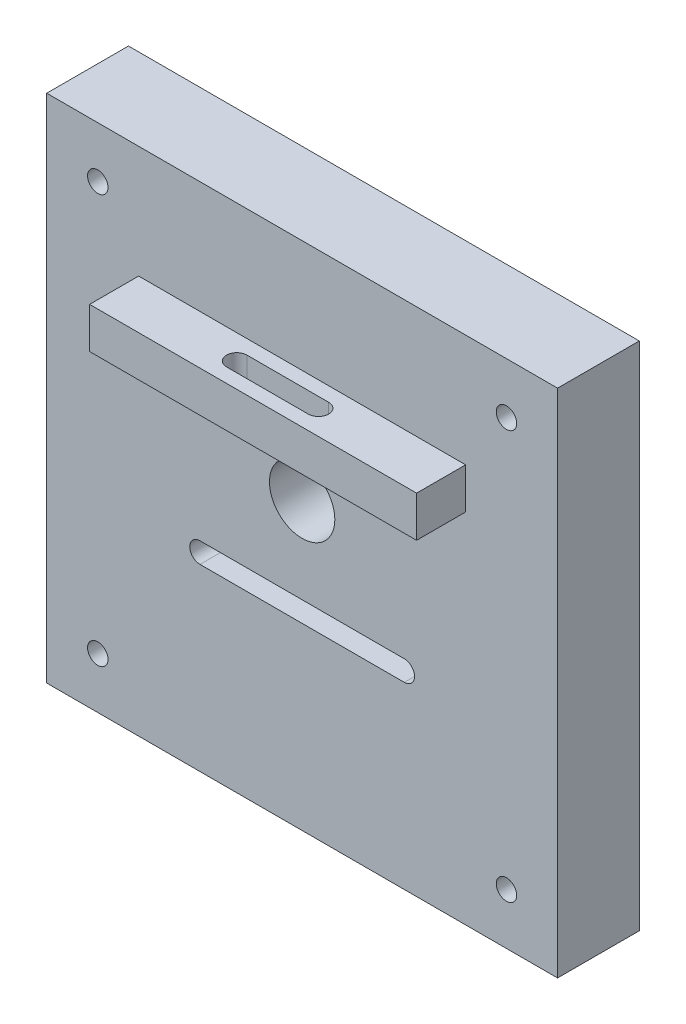
SolidWorks part; units mm, degrees
ref_plane "Front Plane" through (0, 0, 0) normal (0, 0, 1) x (1, 0, 0)
ref_plane "Top Plane" through (0, 0, 0) normal (0, 1, 0) x (1, 0, 0)
ref_plane "Right Plane" through (0, 0, 0) normal (1, 0, 0) x (0, 0, -1)
sketch "Sketch1" plane through (0, 0, 0) normal (0, 0, 1) x (1, 0, 0)
  line L1 (-58.3251, 63.7279) -> (66.6749, 63.7279)
  line L2 (-58.3251, 63.7279) -> (-58.3251, -61.2721)
  line L3 (-58.3251, -61.2721) -> (66.6749, -61.2721)
  line L4 (66.6749, 63.7279) -> (66.6749, -61.2721)
  dimension "D1" = 125
  dimension "D2" = 125
extrude "Boss-Extrude1" add sketch "Sketch1" along normal blind 20
sketch "Sketch2" plane through (0, 0, 20) normal (0, 0, 1) x (1, 0, 0)
  line L0 (-58.3251, 63.7279) -> (-58.3251, -61.2721) construction
  line L1 (66.6749, 63.7279) -> (-58.3251, 63.7279) construction
  circle A0 centre (-45.8251, 51.2279) radius 2.5
  circle A1 centre (54.1749, 51.2279) radius 2.5
  circle A2 centre (54.1749, -48.7721) radius 2.5
  circle A3 centre (-45.8251, -48.7721) radius 2.5
  dimension "D1" = 5
  dimension "D2" = 12.5
  dimension "D3" = 12.5
  dimension "D4" = 2
  dimension "D5" = 2
extrude "Cut-Extrude1" cut sketch "Sketch2" against normal through all
sketch "Sketch3" plane through (0, 0, 20) normal (0, 0, 1) x (1, 0, 0)
  line L0 (-58.3251, 63.7279) -> (-58.3251, -61.2721) construction
  line L1 (-35.8251, 26.2279) -> (44.1749, 26.2279) construction
  line L2 (-35.8251, 26.2279) -> (-35.8251, -23.7721) construction
  line L3 (-35.8251, -23.7721) -> (44.1749, -23.7721) construction
  line L4 (44.1749, 26.2279) -> (44.1749, -23.7721) construction
  line L5 (66.6749, 63.7279) -> (-58.3251, 63.7279) construction
  line L6 (-35.8251, -14.8721) -> (-16.8951, -14.8721) construction
  line L7 (4.1749, 26.2279) -> (4.1749, -12.3721) construction
  line L8 (-20.8251, -12.3721) -> (29.1749, -12.3721)
  line L10 (29.1749, -17.3721) -> (-20.8251, -17.3721)
  line L11 (4.1749, -14.8721) -> (44.1749, -14.8721) construction
  line L12 (4.1749, -17.3721) -> (4.1749, -23.7721) construction
  arc A0 (-20.8251, -12.3721) -> (-20.8251, -17.3721) centre (-20.8251, -14.8721) ccw
  arc A1 (29.1749, -12.3721) -> (29.1749, -17.3721) centre (29.1749, -14.8721) cw
  circle A2 centre (4.1749, 8.6279) radius 8
  point P4 (-58.3251, 1.2279)
  point P7 (-35.8251, 1.2279)
  point P8 (4.1749, 26.2279)
  point P11 (4.1749, 63.7279)
  dimension "D4" = 5
  dimension "D7" = 16
  dimension "D1" = 80
  dimension "D2" = 50
  dimension "D3" = 8.9
  dimension "D5" = 15
  dimension "D6" = 17.6
extrude "Cut-Extrude2" cut sketch "Sketch3" against normal through all
sketch "Sketch4" plane through (0, 0, 0) normal (0, 0, -1) x (-1, 0, 0)
  line L0 (-29.1749, -12.3721) -> (20.8251, -12.3721) construction
  line L1 (-39.1749, -7.3721) -> (30.8251, -7.3721)
  line L2 (-39.1749, -7.3721) -> (-39.1749, -22.3721)
  line L3 (-39.1749, -22.3721) -> (30.8251, -22.3721)
  line L4 (30.8251, -7.3721) -> (30.8251, -22.3721)
  arc A0 (-29.1749, -12.3721) -> (-29.1749, -17.3721) centre (-29.1749, -14.8721) ccw construction
  point P4 (-4.1749, -7.3721)
  point P7 (-4.1749, -12.3721)
  point P11 (-31.6749, -14.8721)
  point P12 (-39.1749, -14.8721)
  dimension "D1" = 15
  dimension "D2" = 70
extrude "Cut-Extrude3" cut sketch "Sketch4" against normal blind 10
fillet "Fillet1" radius 5 4 edges at (-30.8251, -22.3721, 5) (39.1749, -22.3721, 5) (-30.8251, -7.3721, 5) (39.1749, -7.3721, 5)
sketch "Sketch6" plane through (0, 0, 20) normal (0, 0, 1) x (1, 0, 0)
  line L1 (-35.8251, 26.2279) -> (44.1749, 26.2279) construction
  line L2 (-35.8251, 26.2279) -> (-35.8251, -23.7721) construction
  line L3 (-35.8251, -23.7721) -> (44.1749, -23.7721) construction
  line L4 (44.1749, 26.2279) -> (44.1749, -23.7721) construction
  line L6 (-35.8251, -14.8721) -> (-16.8951, -14.8721) construction
  line L7 (4.1749, 26.2279) -> (4.1749, -12.3721) construction
  line L11 (4.1749, -14.8721) -> (44.1749, -14.8721) construction
  line L12 (4.1749, -17.3721) -> (4.1749, -23.7721) construction
  line L13 (-58.3251, -61.2721) -> (66.6749, -61.2721) construction
  line L14 (-58.3251, 63.7279) -> (-58.3251, -61.2721) construction
  line L16 (-35.8251, 26.2279) -> (44.1749, 26.2279)
  line L17 (-35.8251, 26.2279) -> (-35.8251, 36.2279)
  line L18 (-35.8251, 36.2279) -> (44.1749, 36.2279)
  line L19 (44.1749, 26.2279) -> (44.1749, 36.2279)
  point P7 (-35.8251, 1.2279)
  point P10 (4.1749, -61.2721)
  point P29 (-58.3251, 1.2279)
  dimension "D4" = 10
  dimension "D1" = 80
  dimension "D2" = 50
  dimension "D3" = 8.9
extrude "Boss-Extrude2" add sketch "Sketch6" along normal blind 12
sketch "Sketch7" plane through (0, 36.2279, 0) normal (0, 1, 0) x (1, 0, 0)
  line L0 (-35.8251, -26) -> (44.1749, -26) construction
  line L1 (-35.8251, -32) -> (-35.8251, -20) construction
  line L2 (44.1749, -32) -> (44.1749, -20) construction
  line L3 (4.1749, -20) -> (4.1749, -32) construction
  line L4 (44.1749, -20) -> (-35.8251, -20) construction
  line L5 (44.1749, -32) -> (-35.8251, -32) construction
  line L6 (-5.8251, -28.5) -> (14.1749, -28.5)
  line L7 (-5.8251, -23.5) -> (14.1749, -23.5)
  arc A0 (-5.8251, -23.5) -> (-5.8251, -28.5) centre (-5.8251, -26) ccw
  arc A1 (14.1749, -23.5) -> (14.1749, -28.5) centre (14.1749, -26) cw
  dimension "D1" = 5
  dimension "D2" = 30
extrude "Cut-Extrude4" cut sketch "Sketch7" against normal through all
